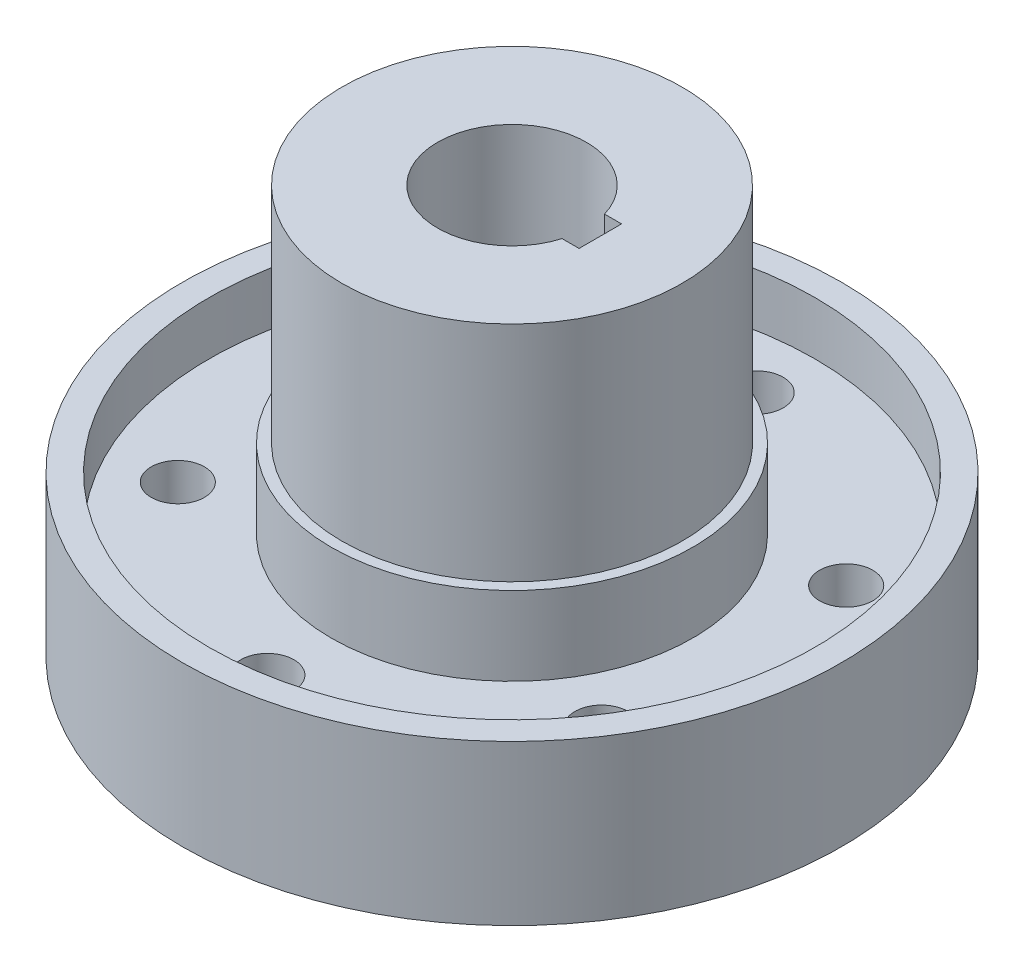
SolidWorks part; units mm, degrees
ref_plane "Front Plane" through (0, 0, 0) normal (0, 0, 1) x (1, 0, 0)
ref_plane "Top Plane" through (0, 0, 0) normal (0, 1, 0) x (1, 0, 0)
ref_plane "Right Plane" through (0, 0, 0) normal (1, 0, 0) x (0, 0, -1)
sketch "Sketch1" plane through (0, 0, 0) normal (0, 1, 0) x (1, 0, 0)
  circle A0 centre (0, 0) radius 155
  dimension "D1" = 310
extrude "Boss-Extrude1" add sketch "Sketch1" along normal blind 75
sketch "Sketch2" plane through (0, 75, 0) normal (0, 1, 0) x (1, 0, 0)
  circle A0 centre (0, 0) radius 142.5
  dimension "D1" = 285
extrude "Cut-Extrude1" cut sketch "Sketch2" against normal blind 25
sketch "Sketch3" plane through (0, 50, 0) normal (0, 1, 0) x (1, 0, 0)
  circle A0 centre (0, 0) radius 85
  dimension "D1" = 170
extrude "Boss-Extrude2" add sketch "Sketch3" along normal blind 37
sketch "Sketch4" plane through (0, 87, 0) normal (0, 1, 0) x (1, 0, 0)
  circle A0 centre (0, 0) radius 80
  dimension "D1" = 160
extrude "Boss-Extrude3" add sketch "Sketch4" along normal blind 105
sketch "Sketch5" plane through (0, 192, 0) normal (0, 1, 0) x (1, 0, 0)
  line L0 (33.541, 10) -> (41.541, 10)
  line L1 (41.541, 10) -> (41.541, -10)
  line L2 (41.541, -10) -> (33.541, -10)
  arc A0 (33.541, 10) -> (33.541, -10) centre (0, 0) ccw
  dimension "D1" = 70
  dimension "D2" = 8
  dimension "D3" = 8
  dimension "D4" = 20
extrude "Cut-Extrude2" cut sketch "Sketch5" against normal through all both and the other way through all
sketch "Sketch6" plane through (0, 0, 0) normal (0, -1, 0) x (1, 0, 0)
  circle A0 centre (0, 0) radius 75
  dimension "D1" = 150
extrude "Boss-Extrude4" add sketch "Sketch6" along normal blind 5
sketch "Sketch7" plane through (0, -5, 0) normal (0, -1, 0) x (1, 0, 0)
  circle A0 centre (0, 0) radius 60
  dimension "D1" = 120
extrude "Cut-Extrude3" cut sketch "Sketch7" against normal blind 58
sketch "Sketch8" plane through (0, 50, 0) normal (0, 1, 0) x (1, 0, 0)
  line L0 (-170.3092, 0) -> (182.3555, 0) construction
  line L1 (0, 158.6783) -> (0, -170.3092) construction
  circle A0 centre (0, 115.0626) radius 12.5
  circle A1 centre (99.6471, 57.5313) radius 12.5
  circle A2 centre (99.6471, -57.5313) radius 12.5
  circle A3 centre (0, -115.0626) radius 12.5
  circle A4 centre (-99.6471, -57.5313) radius 12.5
  circle A5 centre (-99.6471, 57.5313) radius 12.5
  point P20 (0, 0)
  dimension "D1" = 25
  dimension "D2" = 6
extrude "Cut-Extrude4" cut sketch "Sketch8" against normal through all
